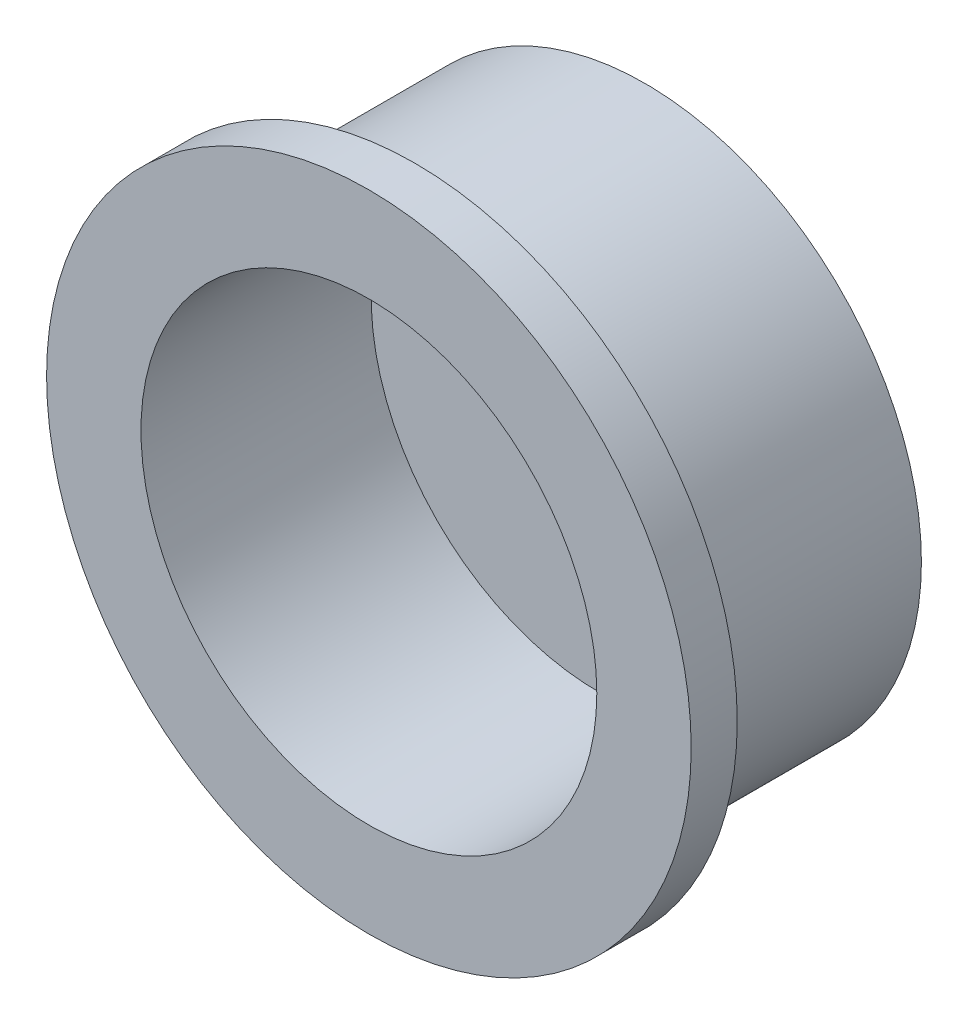
SolidWorks part; units mm, degrees
ref_plane "Спереди" through (0, 0, 0) normal (0, 0, 1) x (1, 0, 0)
ref_plane "Сверху" through (0, 0, 0) normal (0, 1, 0) x (1, 0, 0)
ref_plane "Справа" through (0, 0, 0) normal (1, 0, 0) x (0, 0, -1)
sketch "Эскиз1" plane through (0, 0, 0) normal (0, 0, 1) x (1, 0, 0)
  circle A0 centre (0, 0) radius 6
  dimension "D1" = 12
extrude "Бобышка-Вытянуть1" add sketch "Эскиз1" along normal blind 1 contours A0
sketch "Эскиз2" plane through (0, 0, 1) normal (0, 0, 1) x (1, 0, 0)
  circle A0 centre (0, 0) radius 6
  circle A1 centre (0, 0) radius 4.95
  dimension "D1" = 9.9
extrude "Бобышка-Вытянуть2" add sketch "Эскиз2" along normal blind 5
sketch "Эскиз3" plane through (0, 0, 6) normal (0, 0, 1) x (1, 0, 0)
  circle A0 centre (0, 0) radius 7
  circle A1 centre (0, 0) radius 6 construction
  dimension "D1" = 1
extrude "Бобышка-Вытянуть3" add sketch "Эскиз3" against normal blind 1
sketch "Эскиз5" plane through (0, 0, 6) normal (0, 0, 1) x (1, 0, 0)
  circle A0 centre (0, 0) radius 4.95
  dimension "D1" = 9.9
extrude "Вырез-Вытянуть1" cut sketch "Эскиз5" against normal blind 5
sketch "Эскиз6" plane through (0, 0, 1) normal (0, 0, 1) x (1, 0, 0)
  circle A0 centre (0, 0) radius 1.5
  dimension "D1" = 3
extrude "Вырез-Вытянуть2" cut sketch "Эскиз6" against normal blind 1
